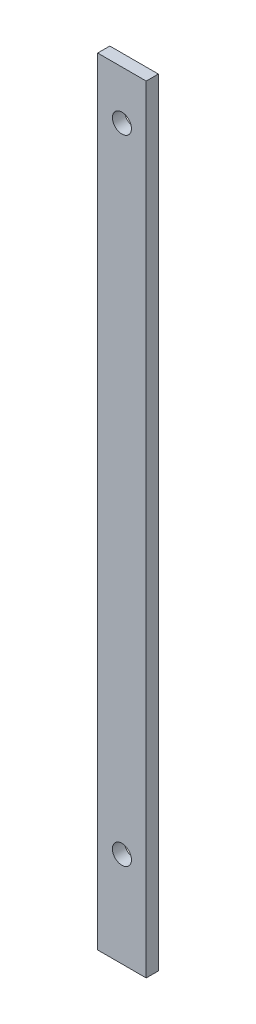
SolidWorks part; units mm, degrees
material "6061 Alloy"
ref_plane "Front Plane" through (0, 0, 0) normal (0, 0, 1) x (1, 0, 0)
ref_plane "Top Plane" through (0, 0, 0) normal (0, 1, 0) x (1, 0, 0)
ref_plane "Right Plane" through (0, 0, 0) normal (1, 0, 0) x (0, 0, -1)
sketch "Sketch1" plane through (0, 0, 0) normal (0, 0, 1) x (1, 0, 0)
  line L0 (-19.05, 101.6) -> (-19.05, -101.6)
  line L1 (-6.35, 101.6) -> (-6.35, -101.6)
  line L2 (-19.05, 101.6) -> (-6.35, 101.6)
  line L3 (-19.05, -101.6) -> (-6.35, -101.6)
  point P3 (-19.05, 0)
  dimension "D1" = 203.2
  dimension "D2" = 12.7
extrude "Boss-Extrude1" add sketch "Sketch1" along normal blind 3.175
sketch "Sketch3" plane through (-19.05, 0, 0) normal (-1, 0, 0) x (0, 0, 1)
  line L0 (0, -81.0395) -> (0, -82.629)
  line L1 (0, -317.5) -> (0, 317.5) construction
  line L2 (0, -81.8343) -> (3.175, -81.8343)
  line L3 (3.175, 101.6) -> (3.175, -101.6) construction
sketch "Sketch5" plane through (0, 0, 3.175) normal (0, 0, 1) x (1, 0, 0)
  line L0 (-19.05, -81.8343) -> (-6.35, -81.8343) construction
  line L1 (-19.05, -81.0395) -> (-19.05, -82.629) construction
  line L2 (-6.35, -101.6) -> (-6.35, 101.6) construction
  line L3 (-12.7, -81.8343) -> (-12.7, -76.7543) construction
  point P6 (-12.7, -81.8343)
  dimension "D1" = 5.08
hole_wizard "#10 Clearance Hole1" positions "Sketch10" profile "Sketch11" hole size "#10" standard "ANSI Inch" end condition through all
sketch "Sketch10" plane through (0, 0, 3.175) normal (0, 0, 1) x (1, 0, 0)
  point P0 (-12.7, -76.7543)
sketch "Sketch11" plane through (-12.7, -76.7543, 3.175) normal (1, 0, 0) x (0, -1, 0)
  line L0 (0, 0) -> (0, 3.175)
  line L1 (0, 3.175) -> (2.4892, 3.175)
  line L2 (2.4892, 3.175) -> (2.4892, 0)
  line L5 (2.4892, 0) -> (0, 0)
  line L11 (0, -6.35) -> (0, 107.95) construction
  dimension "Thru Hole Dia." = 4.9784
  dimension "Thru Hole Depth" = 3.175
sketch "Sketch12" plane through (0, 0, 3.175) normal (0, 0, 1) x (1, 0, 0)
  line L0 (-19.05, 101.6) -> (-6.35, 101.6) construction
  line L1 (-12.7, 101.6) -> (-12.7, 88.9) construction
  dimension "D1" = 12.7
hole_wizard "#10 Clearance Hole2" positions "Sketch13" profile "Sketch14" hole size "#10" standard "ANSI Inch" end condition through all
sketch "Sketch13" plane through (0, 0, 3.175) normal (0, 0, 1) x (1, 0, 0)
  point P0 (-12.7, 88.9)
sketch "Sketch14" plane through (-12.7, 88.9, 3.175) normal (1, 0, 0) x (0, -1, 0)
  line L0 (0, 0) -> (0, 3.175)
  line L1 (0, 3.175) -> (2.4892, 3.175)
  line L2 (2.4892, 3.175) -> (2.4892, 0)
  line L5 (2.4892, 0) -> (0, 0)
  line L11 (0, -6.35) -> (0, 107.95) construction
  dimension "Thru Hole Dia." = 4.9784
  dimension "Thru Hole Depth" = 3.175
